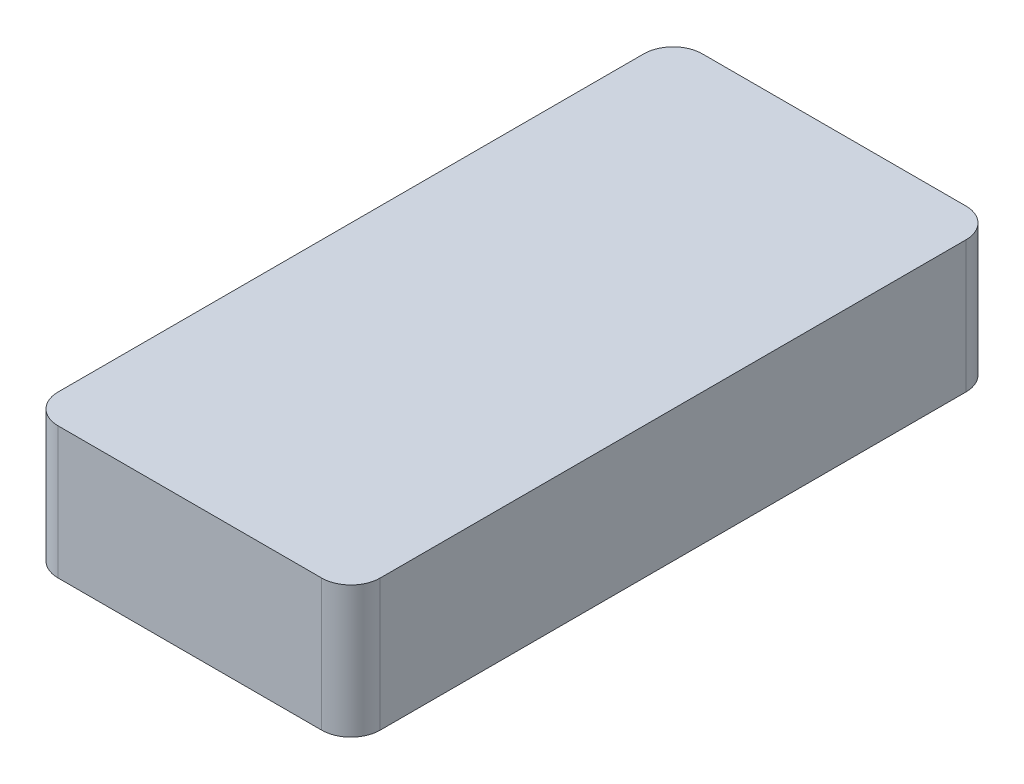
SolidWorks part; units mm, degrees
ref_plane "Front Plane" through (0, 0, 0) normal (0, 0, 1) x (1, 0, 0)
ref_plane "Top Plane" through (0, 0, 0) normal (0, 1, 0) x (1, 0, 0)
ref_plane "Right Plane" through (0, 0, 0) normal (1, 0, 0) x (0, 0, -1)
sketch "Sketch1" plane through (0, 0, 0) normal (0, 1, 0) x (1, 0, 0)
  line L1 (-11, 22) -> (11, 22)
  line L2 (-11, 22) -> (-11, -22)
  line L3 (-11, -22) -> (11, -22)
  line L4 (11, 22) -> (11, -22)
  line L5 (-11, 22) -> (11, -22) construction
  line L6 (-11, -22) -> (11, 22) construction
  point P0 (0, 0)
  dimension "D1" = 22
  dimension "D2" = 44
extrude "Boss-Extrude1" add sketch "Sketch1" along normal blind 9
fillet "Fillet1" radius 2 4 edges at (-11, 4.5, -22) (11, 4.5, -22) (-11, 4.5, 22) (11, 4.5, 22)
